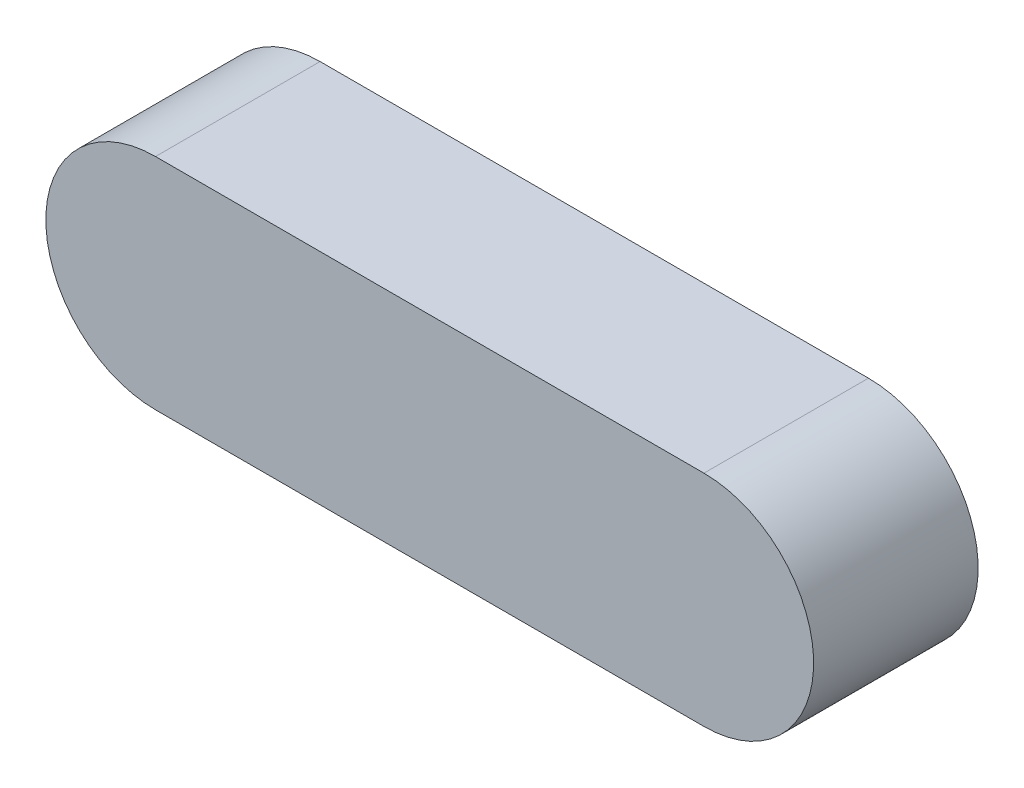
SolidWorks part; units mm, degrees
ref_plane "Front Plane" through (0, 0, 0) normal (0, 0, 1) x (1, 0, 0)
ref_plane "Top Plane" through (0, 0, 0) normal (0, 1, 0) x (1, 0, 0)
ref_plane "Right Plane" through (0, 0, 0) normal (1, 0, 0) x (0, 0, -1)
sketch "Sketch1" plane through (0, 0, 0) normal (0, 0, 1) x (1, 0, 0)
  line L0 (0, 0) -> (20, 0) construction
  line L1 (0, 4) -> (20, 4)
  line L2 (0, -4) -> (20, -4)
  arc A0 (0, 4) -> (0, -4) centre (0, 0) ccw
  arc A1 (20, -4) -> (20, 4) centre (20, 0) ccw
  point P3 (10, 0)
  point P8 (-4, 0)
  point P9 (24, 0)
  dimension "D1" = 28
  dimension "D2" = 8
extrude "Boss-Extrude1" add sketch "Sketch1" along normal blind 6
